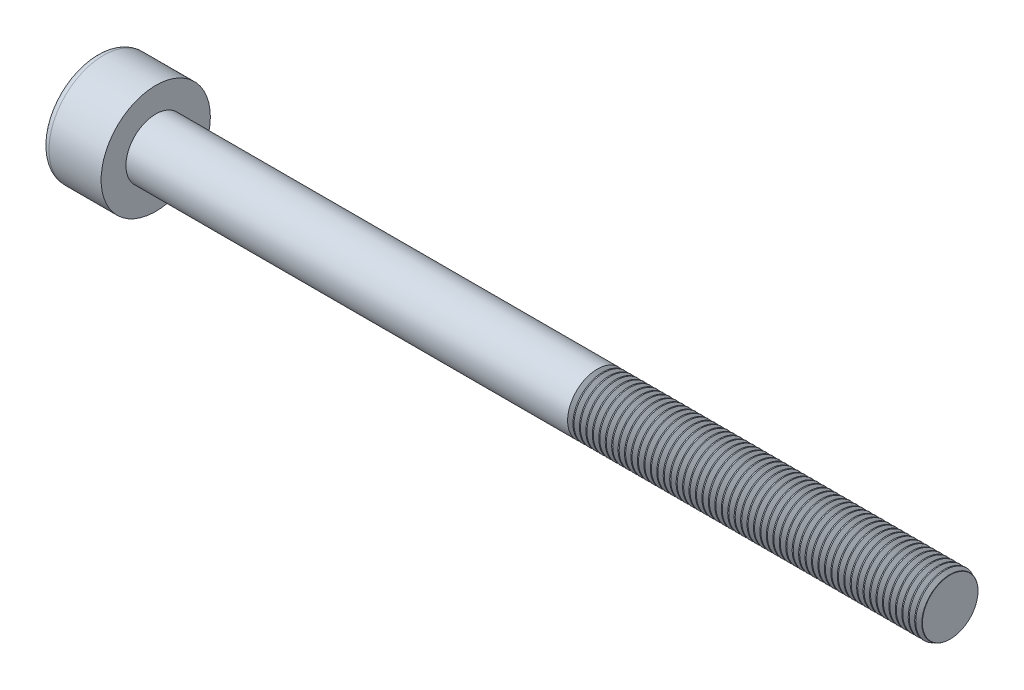
SolidWorks part; units mm, degrees
ref_plane "Front" through (0, 0, 0) normal (0, 0, 1) x (1, 0, 0)
ref_plane "Top" through (0, 0, 0) normal (0, 1, 0) x (1, 0, 0)
ref_plane "Right" through (0, 0, 0) normal (1, 0, 0) x (0, 0, -1)
sketch "Sketch1" plane through (0, 0, 0) normal (1, 0, 0) x (0, 0, -1)
  circle A0 centre (0, 0) radius 2.75
  dimension "dk" = 5.5
extrude "BaseHead" add sketch "Sketch1" along normal blind 3
sketch "Sketch2" plane through (3, 0, 0) normal (1, 0, 0) x (0, 0, -1)
  circle A0 centre (0, 0) radius 1.5
  dimension "d" = 3
extrude "BaseBody" add sketch "Sketch2" along normal blind 40
cosmetic thread "ThreadCosmetic1" [suppressed] parameters "b"=18, "D2"=2.459
sketch "Sketch3" plane through (0, 0, 0) normal (1, 0, 0) x (0, 0, -1)
  line L1 (1.4434, 0) -> (0.7217, 1.25)
  line L2 (0.7217, 1.25) -> (-0.7217, 1.25)
  line L3 (-0.7217, 1.25) -> (-1.4434, 0)
  line L4 (-1.4434, 0) -> (-0.7217, -1.25)
  line L5 (-0.7217, -1.25) -> (0.7217, -1.25)
  line L6 (0.7217, -1.25) -> (1.4434, 0)
  circle A0 centre (0, 0) radius 1.25 construction
  dimension "s" = 2.5
  dimension "e" = 2.8868
extrude "HexagonSocket" cut sketch "Sketch3" along normal blind 1.3
sketch "Sketch4" plane through (-4.1961, 0.75, 0) normal (0, 0, 1) x (-1, 0, 0)
  line L0 (-5.4961, 2) -> (-6.2178, 0.75)
  line L2 (-6.2178, 0.75) -> (-5.4961, 0.75)
  line L3 (-5.4961, 0.75) -> (-5.4961, 2)
  line L4 (-5.0351, 0.75) -> (0.839, 0.75) construction
  line L5 (-47.1961, 0.75) -> (-7.1961, 0.75) construction
  line L6 (-7.1961, 0.75) -> (-4.1961, 0.75) construction
  dimension "m" = 60
revolve "Cut-Revolve1" cut sketch "Sketch4" angle 360 about L4
fillet "HeadFillet" [suppressed] radius 0.1
fillet "TopFillet" radius 0.375 1 edges at (0, 0, -2.75)
chamfer "Chamfer1" distance 0.1 angle 45 1 edges at (43, 0, -1.5)
sketch "Sketch5" plane through (0, 0, 0) normal (0, 0, 1) x (1, 0, 0)
  line L0 (42.9, 1.2657) -> (43.0353, 1.5)
  line L1 (43.0353, 1.5) -> (43.0353, 1.7705)
  line L2 (43.0353, 1.7705) -> (42.7648, 1.7705)
  line L3 (42.7648, 1.7705) -> (42.7648, 1.5)
  line L4 (42.7648, 1.5) -> (42.9, 1.2657)
  line L5 (0, 0) -> (7.8886, 0) construction
  line L6 (42.9, -1.5) -> (42.9, 1.5) construction
  dimension "D1" = 3
  dimension "D2" = 0.2705
revolve "Cut-Revolve10" cut sketch "Sketch5" angle 360 about L5
pattern_linear "LPattern10" count 55 spacing 0.3246 along (-1, 0, 0) of "Cut-Revolve10"
equation "\"r1@TopFillet\" = \"d@Sketch2\" / 8"
equation "\"D1@Chamfer1\" = \"r@HeadFillet\""
equation "\"D1@Sketch5\" = \"d@Sketch2\""
equation "\"D2@Sketch5\" =  ( \"d@Sketch2\" - \"D2@ThreadCosmetic1\" )  / 2"
equation "\"D3@LPattern10\" = \"D2@Sketch5\" * 1.2"
equation "\"D1@LPattern10\" = \"b@ThreadCosmetic1\" / \"D3@LPattern10\""
